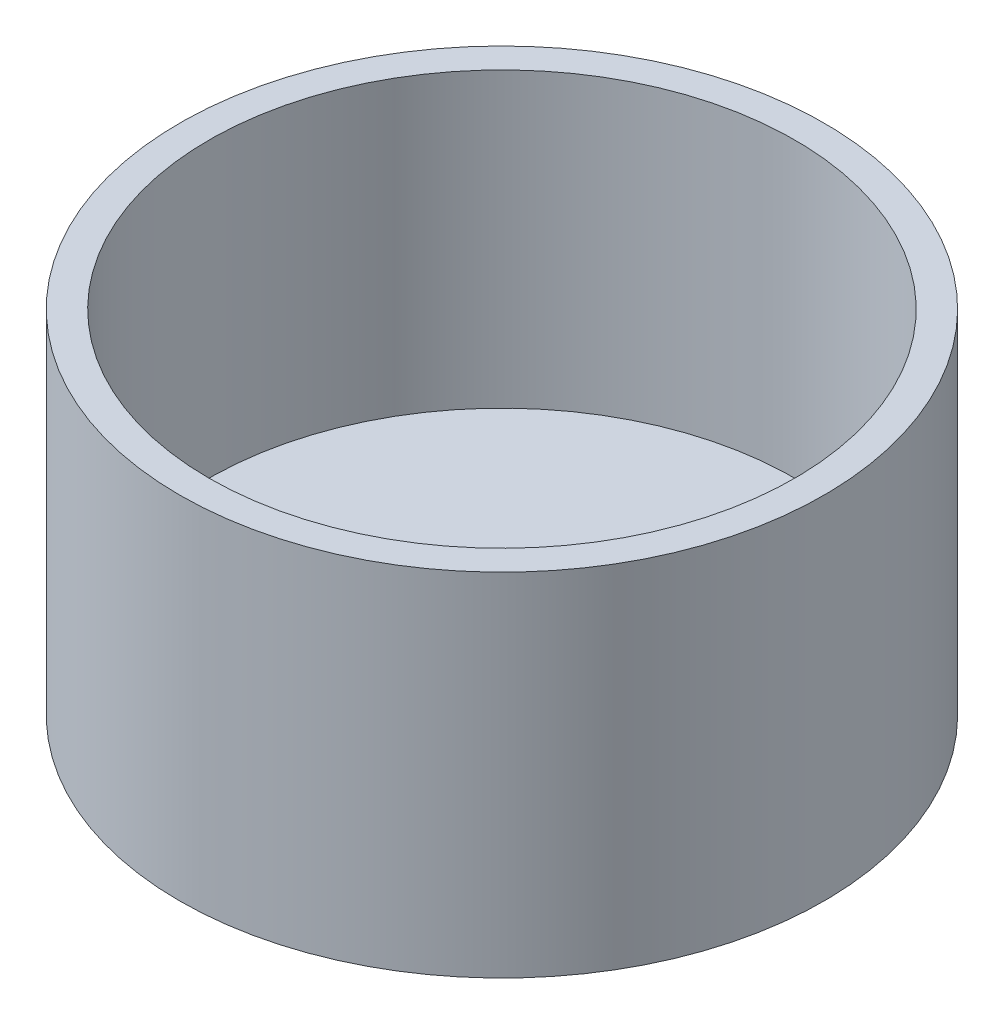
SolidWorks part; units mm, degrees
ref_plane "Front Plane" through (0, 0, 0) normal (0, 0, 1) x (1, 0, 0)
ref_plane "Top Plane" through (0, 0, 0) normal (0, 1, 0) x (1, 0, 0)
ref_plane "Right Plane" through (0, 0, 0) normal (1, 0, 0) x (0, 0, -1)
sketch "Sketch1" plane through (0, 0, 0) normal (0, 1, 0) x (1, 0, 0)
  circle A0 centre (0, 0) radius 2.75
  circle A1 centre (0, 0) radius 0.75
  dimension "D1" = 5.5
  dimension "D2" = 1.5
extrude "Boss-Extrude1" add sketch "Sketch1" along normal blind 3
sketch "Sketch4" plane through (0, 3, 0) normal (0, 1, 0) x (1, 0, 0)
  circle A0 centre (0, 0) radius 2.75
  circle A1 centre (0, 0) radius 2.5
  dimension "D1" = 5.5
  dimension "D2" = 5
extrude "Cut-Extrude2" cut sketch "Sketch4" against normal blind 2.5 contours A1
